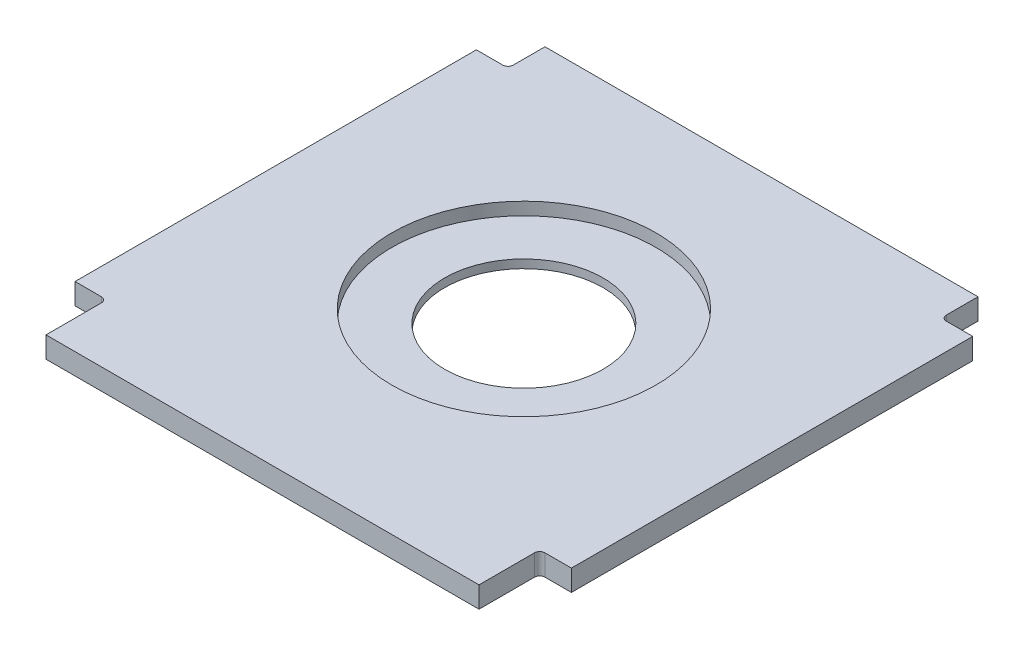
SolidWorks part; units mm, degrees
ref_plane "Front Plane" through (0, 0, 0) normal (0, 0, 1) x (1, 0, 0)
ref_plane "Top Plane" through (0, 0, 0) normal (0, 1, 0) x (1, 0, 0)
ref_plane "Right Plane" through (0, 0, 0) normal (1, 0, 0) x (0, 0, -1)
sketch "Sketch1" plane through (0, 0, 0) normal (0, 1, 0) x (1, 0, 0)
  line L5 (-41, -38) -> (41, 38) construction
  line L6 (-41, 38) -> (41, -38) construction
  line L8 (-41, 38) -> (-41, 45)
  line L9 (-41, 45) -> (41, 45)
  line L10 (41, 38) -> (41, 45)
  line L12 (-41, -38) -> (-41, -49.5)
  line L13 (-41, -49.5) -> (41, -49.5)
  line L14 (41, -38) -> (41, -49.5)
  line L15 (-41, 38) -> (-47, 38)
  line L17 (-41, -38) -> (-47, -38)
  line L18 (-47, 38) -> (-47, -38)
  line L19 (41, 38) -> (47, 38)
  line L21 (41, -38) -> (47, -38)
  line L22 (47, 38) -> (47, -38)
  point P0 (0, 0)
  dimension "D1" = 82
  dimension "D2" = 76
  dimension "D3" = 6
  dimension "D4" = 11.5
  dimension "D5" = 7
  dimension "D6" = 6
extrude "Boss-Extrude1" add sketch "Sketch1" along normal blind 4
sketch "Sketch2" plane through (0, 4, 0) normal (0, 1, 0) x (1, 0, 0)
  circle A0 centre (0, 0) radius 15
  dimension "D1" = 30
extrude "Cut-Extrude1" cut sketch "Sketch2" against normal up to next
fillet "Fillet1" radius 1 4 edges at (-41, 2, 38) (-41, 2, -38) (41, 2, -38) (41, 2, 38)
sketch "Sketch4" plane through (0, 4, 0) normal (0, 1, 0) x (1, 0, 0)
  circle A0 centre (0, 0) radius 15
  circle A1 centre (0, 0) radius 25
  dimension "D1" = 50
  dimension "D2" = 30
extrude "Cut-Extrude2" cut sketch "Sketch4" against normal blind 2.4
